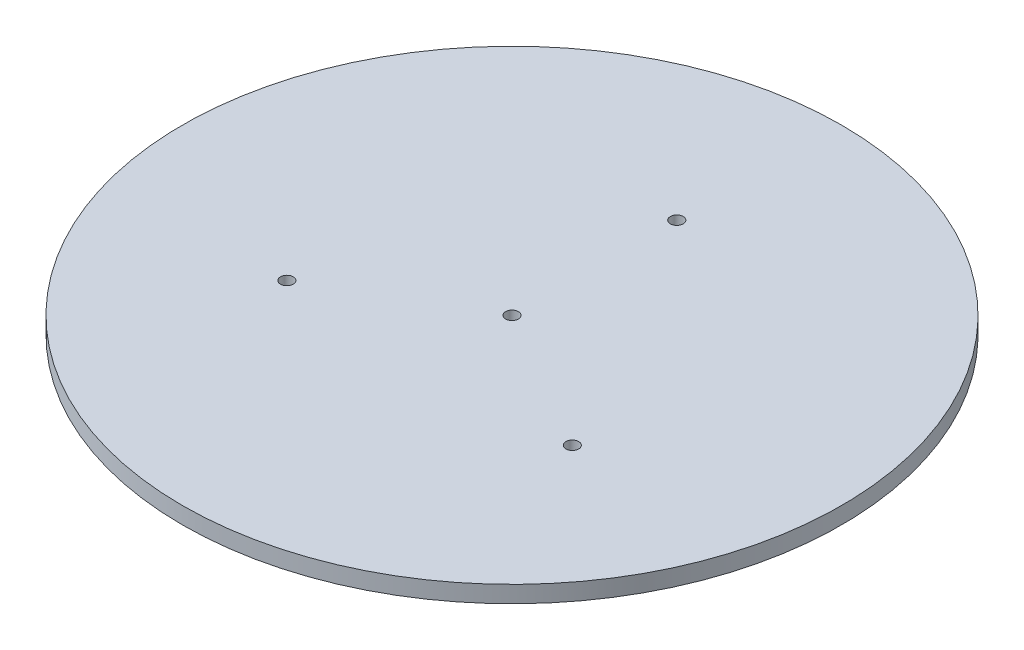
SolidWorks part; units mm, degrees
ref_plane "Front Plane" through (0, 0, 0) normal (0, 0, 1) x (1, 0, 0)
ref_plane "Top Plane" through (0, 0, 0) normal (0, 1, 0) x (1, 0, 0)
ref_plane "Right Plane" through (0, 0, 0) normal (1, 0, 0) x (0, 0, -1)
sketch "Sketch1" plane through (0, 0, 0) normal (0, 1, 0) x (1, 0, 0)
  line L0 (0, 0) -> (0, 124.6188) construction
  circle A0 centre (0, 0) radius 124.6188
  circle A1 centre (0, 62.3094) radius 2.4257
  circle A2 centre (53.9615, -31.1547) radius 2.4257
  circle A3 centre (-53.9615, -31.1547) radius 2.4257
  circle A4 centre (0, 0) radius 2.4257
  point P13 (0, 0)
  dimension "D1" = 249.2375
  dimension "D2" = 4.8514
  dimension "D4" = 4.8514
  dimension "D3" = 3
extrude "Boss-Extrude1" add sketch "Sketch1" along normal blind 6.35
